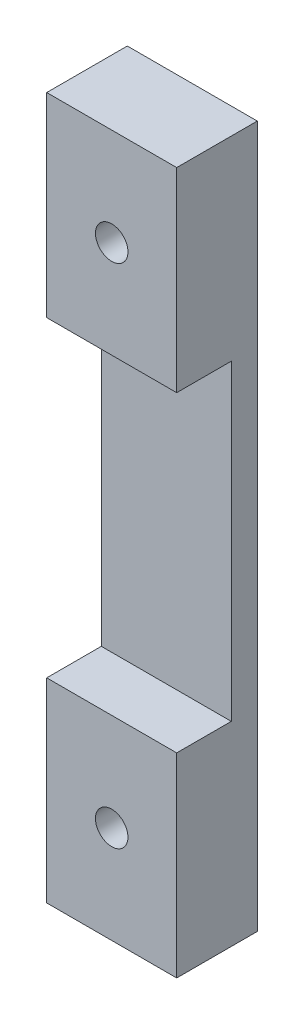
SolidWorks part; units mm, degrees
material "自訂玻璃纖維"
ref_plane "前基準面" through (0, 0, 0) normal (0, 0, 1) x (1, 0, 0)
ref_plane "上基準面" through (0, 0, 0) normal (0, 1, 0) x (1, 0, 0)
ref_plane "右基準面" through (0, 0, 0) normal (1, 0, 0) x (0, 0, -1)
sketch "草圖1" plane through (0, 0, 0) normal (0, 0, 1) x (1, 0, 0)
  line L1 (-61.6356, 53.75) -> (-51.6356, 53.75)
  line L2 (-61.6356, 53.75) -> (-61.6356, -0.25)
  line L3 (-61.6356, -0.25) -> (-51.6356, -0.25)
  line L4 (-51.6356, 53.75) -> (-51.6356, -0.25)
  dimension "D1" = 10
  dimension "D2" = 54
extrude "填料-伸長1" add sketch "草圖1" along normal blind 2
sketch "草圖2" plane through (0, 0, 2) normal (0, 0, 1) x (1, 0, 0)
  line L0 (-61.6356, 38.75) -> (-51.6356, 38.75)
  line L1 (-61.6356, 53.75) -> (-61.6356, -0.25) construction
  line L2 (-51.6356, -0.25) -> (-51.6356, 53.75) construction
  line L3 (-51.6356, 53.75) -> (-61.6356, 53.75) construction
  line L4 (-61.6356, 14.75) -> (-51.6356, 14.75)
  line L5 (-61.6356, -0.25) -> (-51.6356, -0.25) construction
  line L6 (-61.6356, 38.75) -> (-61.6356, 53.75)
  line L7 (-61.6356, 53.75) -> (-51.6356, 53.75)
  line L8 (-51.6356, 53.75) -> (-51.6356, 38.75)
  line L9 (-61.6356, -0.25) -> (-61.6356, 14.75)
  line L10 (-61.6356, 14.75) -> (-61.6626, 14.7284)
  line L11 (-51.6356, 14.75) -> (-51.6356, -0.25)
  line L12 (-51.6356, -0.25) -> (-61.6356, -0.25)
  line M3 (-61.6356, 53.75) -> (-61.6356, -0.25)
  line M4 (-61.6356, -0.25) -> (-51.6356, -0.25)
  line M5 (-51.6356, -0.25) -> (-51.6356, 53.75)
  line M6 (-51.6356, 53.75) -> (-61.6356, 53.75)
  dimension "D1" = 15
  dimension "D2" = 15
extrude "填料-伸長2" add sketch "草圖2" along normal blind 4.2 contours L4 M3 M4 M5 | L0 M3 M5 M6
sketch "草圖3" plane through (0, 0, 6.2) normal (0, 0, 1) x (1, 0, 0)
  circle A0 centre (-56.6356, 7.25) radius 1.25
  circle A1 centre (-56.6356, 46.25) radius 1.25
  dimension "D1" = 2.5
  dimension "D2" = 2.5
extrude "除料-伸長1" cut sketch "草圖3" against normal through all
